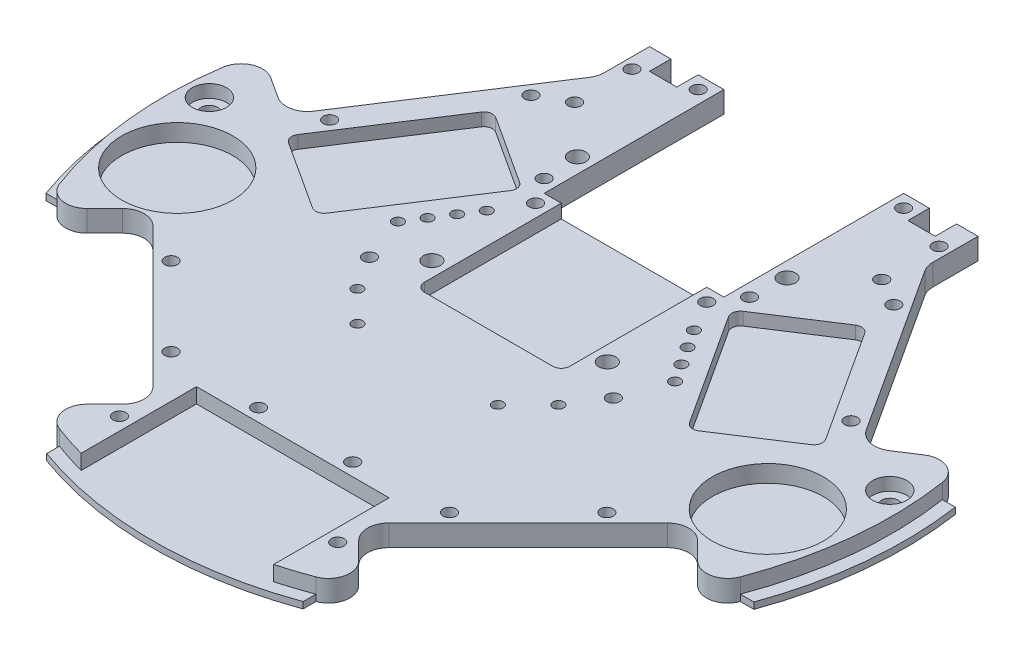
SolidWorks part; units mm, degrees
material "7079 Alloy"
ref_plane "Front" through (0, 0, 0) normal (0, 0, 1) x (1, 0, 0)
ref_plane "Top" through (0, 0, 0) normal (0, 1, 0) x (1, 0, 0)
ref_plane "Right" through (0, 0, 0) normal (1, 0, 0) x (0, 0, -1)
sketch "Sketch1" plane through (0, 0, 0) normal (0, 1, 0) x (1, 0, 0)
  line L0 (0, 0) -> (85, 0)
  line L1 (0, 85) -> (0, 0)
  line L2 (-85, 0) -> (0, 0)
  line L3 (0, -85) -> (0, 0)
  line L4 (0, 0) -> (60.1041, -60.1041)
  line L5 (0, 0) -> (-60.1041, -60.1041)
  line L6 (0, 0) -> (71.287, 46.2943)
  line L7 (0, 0) -> (-71.287, 46.2943)
  line L8 (54.5179, 65.2134) -> (38.3816, 54.7344)
  line L9 (38.3816, 54.7344) -> (67.2475, 10.2848)
  line L10 (67.2475, 10.2848) -> (82.5581, 20.2277)
  line L11 (76.5484, -36.9505) -> (63.6396, -24.0416)
  line L12 (63.6396, -24.0416) -> (24.0416, -63.6396)
  line L13 (24.0416, -63.6396) -> (36.9505, -76.5484)
  line L14 (-36.9505, -76.5484) -> (-24.0416, -63.6396)
  line L15 (-24.0416, -63.6396) -> (-63.6396, -24.0416)
  line L16 (-63.6396, -24.0416) -> (-76.5484, -36.9505)
  line L17 (-82.5581, 20.2277) -> (-67.2475, 10.2848)
  line L18 (-67.2475, 10.2848) -> (-38.3816, 54.7344)
  line L19 (-38.3816, 54.7344) -> (-54.5179, 65.2134)
  line L20 (-54.5179, 65.2134) -> (2.4596, 65.2134)
  line L21 (2.4596, 65.2134) -> (54.5179, 65.2134)
  line L22 (-38.3816, 54.7344) -> (0, 54.7344)
  line L23 (0, 54.7344) -> (38.3816, 54.7344)
  line L24 (38.3816, 54.7344) -> (38.3816, 75.841)
  line L25 (-38.3816, 75.841) -> (0, 75.841)
  line L26 (-38.3816, 75.841) -> (-38.3816, 54.7344)
  line L27 (0, 75.841) -> (38.3816, 75.841)
  circle A0 centre (0, 0) radius 85
  dimension "D1" = 170
  dimension "D2" = 33
  dimension "D3" = 33
  dimension "D4" = 45
  dimension "D5" = 23
  dimension "D6" = 23
  dimension "D7" = 23
  dimension "D8" = 23
  dimension "D9" = 25
  dimension "D10" = 28
  dimension "D11" = 28
  dimension "D12" = 28
  dimension "D13" = 28
  dimension "D14" = 28
  dimension "D15" = 28
  dimension "D16" = 25
sketch "Sketch2" plane through (0, 0, 0) normal (0, 1, 0) x (1, 0, 0)
  line L0 (82.5581, 20.2277) -> (67.2475, 10.2848)
  line L1 (67.2475, 10.2848) -> (38.3816, 54.7344)
  line L2 (76.5484, -36.9505) -> (63.6396, -24.0416)
  line L3 (63.6396, -24.0416) -> (24.0416, -63.6396)
  line L4 (24.0416, -63.6396) -> (36.9505, -76.5484)
  line L5 (-36.9505, -76.5484) -> (-24.0416, -63.6396)
  line L6 (-24.0416, -63.6396) -> (-63.6396, -24.0416)
  line L7 (-63.6396, -24.0416) -> (-76.5484, -36.9505)
  line L8 (-82.5581, 20.2277) -> (-67.2475, 10.2848)
  line L9 (-67.2475, 10.2848) -> (-38.3816, 54.7344)
  line L10 (-38.3816, 54.7344) -> (-38.3816, 66.7344)
  line L11 (-38.3816, 75.841) -> (-38.3816, 54.7344) construction
  line L12 (-38.3816, 66.7344) -> (38.3816, 66.7344)
  line L13 (38.3816, 54.7344) -> (38.3816, 75.841) construction
  line L14 (38.3816, 66.7344) -> (38.3816, 54.7344)
  arc A0 (82.5581, 20.2277) -> (76.5484, -36.9505) centre (0, 0) cw
  arc A1 (36.9505, -76.5484) -> (-36.9505, -76.5484) centre (0, 0) cw
  arc A2 (-76.5484, -36.9505) -> (-82.5581, 20.2277) centre (0, 0) cw
  dimension "D1" = 12
extrude "Extrude1" add sketch "Sketch2" against normal blind 5
sketch "Sketch3" plane through (0, 0, 0) normal (0, 1, 0) x (1, 0, 0)
  line L0 (-21, 71.7344) -> (-21, 24.7344)
  line L1 (-21, 24.7344) -> (21, 24.7344)
  line L2 (21, 24.7344) -> (21, 71.7344)
  line L3 (21, 71.7344) -> (-21, 71.7344)
  line L4 (38.3816, 66.7344) -> (-38.3816, 66.7344) construction
  dimension "D1" = 21
  dimension "D2" = 21
  dimension "D3" = 42
  dimension "D4" = 5
extrude "Extrude2" cut sketch "Sketch3" against normal up to surface (5 mm away) up to face at (0, -5, 6.7435)
sketch "Sketch4" plane through (0, 0, 0) normal (0, 1, 0) x (-1, 0, 0)
  line L0 (17, 9.2656) -> (17, -30.7344)
  line L2 (17, 9.2656) -> (-17, 9.2656)
  line L3 (17, -30.7344) -> (-17, -30.7344)
  line L4 (-17, -30.7344) -> (-17, 9.2656)
  line L5 (21, -24.7344) -> (-21, -24.7344) construction
  dimension "D1" = 34
  dimension "D2" = 17
  dimension "D3" = 34
  dimension "D4" = 40
extrude "Extrude3" cut sketch "Sketch4" against normal blind 3.2
sketch "Sketch5" plane through (0, 0, 0) normal (0, 1, 0) x (1, 0, 0)
  line L0 (43.4707, -6.3484) -> (62.7601, 6.1783)
  line L1 (62.7601, 6.1783) -> (43.6977, 35.5318)
  line L2 (43.6977, 35.5318) -> (24.4083, 23.0051)
  line L3 (24.4083, 23.0051) -> (43.4707, -6.3484)
  line L5 (67.2475, 10.2848) -> (38.3816, 54.7344) construction
  line L6 (82.5581, 20.2277) -> (67.2475, 10.2848) construction
  dimension "D1" = 6
  dimension "D2" = 35
  dimension "D3" = 23
  dimension "D4" = 1
extrude "Extrude4" cut sketch "Sketch5" against normal blind 3
mirror "Mirror1" about plane through (0, 0, 0) normal (1, 0, 0) of "Extrude4"
sketch "Sketch6" plane through (0, 0, 0) normal (0, 1, 0) x (1, 0, 0)
  line L0 (0, 0) -> (71.287, 46.2943) construction
  line L1 (38.3816, 54.7344) -> (67.2475, 10.2848) construction
  line L2 (63.6396, -24.0416) -> (24.0416, -63.6396) construction
  line L3 (0, 0) -> (60.1041, -60.1041) construction
  circle A0 centre (42.4013, 43.0364) radius 1.5
  circle A1 centre (60.919, 14.5216) radius 1.5
  circle A2 centre (50.9117, -32.5269) radius 1.5
  circle A3 centre (32.5269, -50.9117) radius 1.5
  dimension "D1" = 3
  dimension "D2" = 3
  dimension "D3" = 3
  dimension "D4" = 3
  dimension "D6" = 3
  dimension "D8" = 3
  dimension "D9" = 3
  dimension "D10" = 13
  dimension "D11" = 13
  dimension "D12" = 3
  dimension "D5" = 13
  dimension "D7" = 21
extrude "Extrude5" cut sketch "Sketch6" against normal up to surface (5 mm away) up to face at (0, -5, -3.7521)
mirror "Mirror2" about plane through (0, 0, 0) normal (1, 0, 0) of "Extrude5"
sketch "Sketch7" plane through (0, 0, 0) normal (0, 1, 0) x (-1, 0, 0)
  line L0 (-38.3816, -66.7344) -> (-21, -66.7344) construction
  line L1 (-21, -24.7344) -> (-21, -66.7344) construction
  line L2 (-17, -24.7344) -> (-21, -24.7344) construction
  circle A0 centre (-24, -63.7344) radius 1.5
  circle A1 centre (-24, -27.7344) radius 1.5
  dimension "D2" = 3
  dimension "D3" = 3
  dimension "D4" = 3
  dimension "D5" = 3
  dimension "D6" = 3
  dimension "D1" = 3
extrude "Extrude6" cut sketch "Sketch7" against normal up to surface (5 mm away) up to face at (-50.9117, -5, 31.0269)
mirror "Mirror3" about plane through (0, 0, 0) normal (1, 0, 0) of "Extrude6"
sketch "Sketch8" plane through (0, 0, 0) normal (0, 1, 0) x (1, 0, 0)
  line L0 (33.3816, 68.7344) -> (33.3816, 61.7344)
  line L1 (33.3816, 61.7344) -> (27, 61.7344)
  line L2 (27, 61.7344) -> (27, 68.7344)
  line L3 (27, 68.7344) -> (33.3816, 68.7344)
  line L4 (38.3816, 54.7344) -> (38.3816, 66.7344) construction
  line L5 (38.3816, 66.7344) -> (21, 66.7344) construction
  circle A0 centre (24, 63.7344) radius 1.5 construction
  dimension "D1" = 5
  dimension "D2" = 3
  dimension "D3" = 2
  dimension "D4" = 5
extrude "Extrude7" cut sketch "Sketch8" against normal up to surface (5 mm away) up to face at (-24, -5, -65.2344)
mirror "Mirror4" about plane through (0, 0, 0) normal (1, 0, 0) of "Extrude7"
sketch "Sketch9" plane through (0, 0, 0) normal (0, 1, 0) x (1, 0, 0)
  line L0 (38.3816, 66.7344) -> (33.3816, 66.7344) construction
  line L1 (38.3816, 54.7344) -> (38.3816, 66.7344) construction
  circle A0 centre (35.8816, 60.1344) radius 1.5
  circle A1 centre (35.8816, 46.7344) radius 1.5
  dimension "D1" = 3
  dimension "D2" = 3
  dimension "D3" = 6.6
  dimension "D4" = 13.4
  dimension "D5" = 2.5
extrude "Extrude8" cut sketch "Sketch9" against normal up to surface (5 mm away) up to face at (-24, -5, -29.2344)
mirror "Mirror5" about plane through (0, 0, 0) normal (1, 0, 0) of "Extrude8"
fillet "Fillet1" radius 5 14 edges at (-38.3816, -2.5, -54.7344) (-67.2475, -2.5, -10.2848) (-82.5581, -2.5, -20.2277) (-76.5484, -2.5, 36.9505) (-63.6396, -2.5, 24.0416) (-24.0416, -2.5, 63.6396) (-36.9505, -2.5, 76.5484) (36.9505, -2.5, 76.5484) (24.0416, -2.5, 63.6396) (63.6396, -2.5, 24.0416) (76.5484, -2.5, 36.9505) (82.5581, -2.5, -20.2277) (67.2475, -2.5, -10.2848) (38.3816, -2.5, -54.7344)
fillet "Fillet2" radius 2 10 edges at (-17, -1.6, 9.2656) (17, -1.6, 9.2656) (-43.4707, -1.5, 6.3484) (-24.4083, -1.5, -23.0051) (-43.6977, -1.5, -35.5318) (-62.7601, -1.5, -6.1783) (43.4707, -1.5, 6.3484) (24.4083, -1.5, -23.0051) (43.6977, -1.5, -35.5318) (62.7601, -1.5, -6.1783)
sketch "Sketch11" plane through (0, 0, 0) normal (0, 1, 0) x (1, 0, 0)
  line L3 (-21, 24.7344) -> (-21, 66.7344) construction
  line L4 (21, 24.7344) -> (21, 66.7344) construction
  circle A2 centre (24.5, 36) radius 2
  circle A3 centre (-24.5, 36) radius 2
  dimension "D7" = 4
  dimension "D8" = 4
  dimension "D9" = 3.5
  dimension "D10" = 3.5
extrude "Extrude10" cut sketch "Sketch11" against normal up to surface (5 mm away) up to face at (-35.8816, -5, -61.6344)
sketch "Sketch14" plane through (0, 0, 0) normal (0, 1, 0) x (1, 0, 0)
  line L0 (25.4976, 21.3278) -> (42.3814, -4.671) construction
  line L1 (42.0204, 34.4425) -> (26.0856, 24.0944) construction
  line L2 (25.4976, 21.3278) -> (42.3814, -4.671) construction
  line L5 (64.5243, 14.4782) -> (39.1882, 53.4923) construction
  line L6 (27.5772, -60.1041) -> (60.1041, -27.5772) construction
  line L7 (67.1751, -27.5772) -> (71.3305, -31.7326) construction
  circle A0 centre (24.2035, 14.5256) radius 1.25
  circle A1 centre (29.6499, 6.1389) radius 1.25
  circle A2 centre (23.483, -16.4119) radius 1.25
  circle A3 centre (16.4119, -23.483) radius 1.25
  circle A4 centre (26.9267, 10.3322) radius 1.25
  circle A5 centre (32.3731, 1.9455) radius 1.25
  dimension "D1" = 2.5
  dimension "D3" = 7
  dimension "D4" = 2.5
  dimension "D7" = 33.79
  dimension "D9" = 2.5
  dimension "D10" = 33.79
  dimension "D12" = 10
  dimension "D8" = 2.5
  dimension "D14" = 2.5
  dimension "D16" = 2.5
  dimension "D2" = 4.79
  dimension "D5" = 4.79
  dimension "D6" = 10
  dimension "D11" = 33.79
  dimension "D13" = 23
  dimension "D15" = 5
  dimension "D17" = 5
  dimension "D18" = 4.79
  dimension "D19" = 4.79
sketch "Sketch15" plane through (0, 0, 0) normal (0, 1, 0) x (1, 0, 0)
  circle A0 centre (69, -13) radius 13
  dimension "D1" = 26
  dimension "D2" = 13
  dimension "D3" = 69
extrude "Extrude13" cut sketch "Sketch15" against normal blind 4
mirror "Mirror7" about plane through (0, 0, 0) normal (1, 0, 0) of "Extrude13"
sketch "Sketch16" plane through (0, 0, 0) normal (0, 1, 0) x (1, 0, 0)
  line L1 (-22.5, -55) -> (22.5, -55)
  line L2 (-22.5, -55) -> (-22.5, -95)
  line L3 (-22.5, -95) -> (22.5, -95)
  line L4 (22.5, -55) -> (22.5, -95)
  dimension "D1" = 22.5
  dimension "D2" = 22.5
  dimension "D3" = 55
  dimension "D4" = 40
extrude "Extrude14" cut sketch "Sketch16" against normal blind 3.5
sketch "Sketch17" plane through (0, 0, 0) normal (0, 1, 0) x (1, 0, 0)
  line L0 (22.5, -81.968) -> (22.5, -55) construction
  line L1 (-22.5, -55) -> (-22.5, -81.968) construction
  circle A0 centre (25.5, -70) radius 1.5
  circle A1 centre (-25.5, -70) radius 1.5
  dimension "D1" = 3
  dimension "D2" = 3
  dimension "D3" = 3
  dimension "D4" = 3
  dimension "D5" = 70
extrude "Extrude16" cut sketch "Sketch17" against normal up to surface (5 mm away) up to face at (-24.5, -5, -38)
sketch "Sketch18" plane through (0, 0, 0) normal (0, 1, 0) x (-1, 0, 0)
  line L0 (-22.5, 55) -> (22.5, 55) construction
  line L1 (-22.5, 55) -> (22.5, 55) construction
  circle A0 centre (-11, 52) radius 1.5
  circle A1 centre (11, 52) radius 1.5
  dimension "D1" = 3
  dimension "D2" = 3
  dimension "D3" = 3
  dimension "D4" = 3
  dimension "D5" = 11
  dimension "D6" = 11
extrude "Extrude17" cut sketch "Sketch18" against normal up to surface (5 mm away) up to face at (-25.5, -5, 68.5)
sketch "Sketch20" plane through (0, 0, 0) normal (0, 1, 0) x (1, 0, 0)
  circle A0 centre (20.5, -2) radius 2
  circle A1 centre (-20.5, -2) radius 2
  dimension "D1" = 4
  dimension "D2" = 4
  dimension "D3" = 20.5
  dimension "D4" = 20.5
  dimension "D5" = 2
  dimension "D6" = 2
extrude "Extrude19" cut sketch "Sketch20" against normal up to surface (5 mm away) up to face at (-11, -5, 50.5)
sketch "Sketch23" plane through (0, -5, 0) normal (0, -1, 0) x (1, 0, 0)
  line L0 (84.0358, -12.7663) -> (87.0358, -12.7663)
  line L1 (79.5452, 29.9593) -> (82.7082, 29.9593)
  arc A0 (79.5452, 29.9593) -> (84.0358, -12.7663) centre (0, 0) cw
  arc A1 (84.0358, -12.7663) -> (79.5452, 29.9593) centre (0, 0) ccw construction
  arc A2 (87.0358, -12.7663) -> (82.7082, 29.9593) centre (0, 0) ccw
  dimension "D1" = 3
extrude "Extrude24" add sketch "Sketch23" against normal blind 1.5
mirror "Mirror8" about plane through (0, 0, 0) normal (1, 0, 0) of "Extrude24"
sketch "Sketch24" plane through (0, -5, 0) normal (0, -1, 0) x (1, 0, 0)
  line L0 (-29.9593, 79.5452) -> (-29.9593, 82.5452)
  line L1 (29.9593, 82.5452) -> (29.9593, 79.5452)
  arc A0 (29.9593, 79.5452) -> (-29.9593, 79.5452) centre (0, 0) ccw
  arc A1 (29.9593, 79.5452) -> (-29.9593, 79.5452) centre (0, 0) ccw construction
  arc A2 (-29.9593, 82.5452) -> (29.9593, 82.5452) centre (0, 0) cw
  dimension "D1" = 3
extrude "Extrude25" add sketch "Sketch24" against normal blind 1.5
sketch "Sketch27" plane through (0, 0, 0) normal (0, 1, 0) x (1, 0, 0)
  line L1 (17, 24.7344) -> (21, 24.7344) construction
  line L2 (17, -7.2656) -> (17, 24.7344) construction
  line L3 (-17, 24.7344) -> (-17, -7.2656) construction
  circle A0 centre (20, 21.7344) radius 1.5
  circle A1 centre (-20, 21.7344) radius 1.5
  dimension "D1" = 3
  dimension "D2" = 3
  dimension "D4" = 3
  dimension "D3" = 3
  dimension "D5" = 3
extrude "Extrude26" cut sketch "Sketch27" against normal up to surface (5 mm away) up to face at (-20.5, -5, 0)
sketch "Sketch28" plane through (0, 0, 0) normal (0, 1, 0) x (1, 0, 0)
  circle A0 centre (28.5, -8.6) radius 1.5
  circle A1 centre (11, -52) radius 1.5 construction
  circle A2 centre (-28.5, -8.6) radius 1.5
  circle A3 centre (-11, -52) radius 1.5 construction
  dimension "D2" = 17.5
  dimension "D3" = 3
  dimension "D5" = 3
  dimension "D1" = 43.4
  dimension "D4" = 17.5
extrude "Extrude27" cut sketch "Sketch28" against normal up to surface (5 mm away) up to face at (-20, -5, -23.2344)
sketch "Sketch29" plane through (0, 0, 0) normal (0, 1, 0) x (1, 0, 0)
  circle A0 centre (-79.5, 5) radius 4
  circle A1 centre (79.5, 5) radius 4
  dimension "D2" = 79.5
  dimension "D4" = 8
  dimension "D5" = 8
  dimension "D1" = 5
  dimension "D3" = 79.5
extrude "Extrude28" cut sketch "Sketch29" against normal blind 3
sketch "Sketch30" plane through (0, -3, 0) normal (0, 1, 0) x (1, 0, 0)
  circle A0 centre (79.5, 5) radius 2
  circle A1 centre (-79.5, 5) radius 2
  dimension "D1" = 4
  dimension "D2" = 4
extrude "Extrude29" cut sketch "Sketch30" against normal up to surface (2 mm away) up to face at (-28.5, -5, 7.1)
extrude "Extrude30" cut sketch "Sketch14" against normal up to surface (5 mm away) up to face at (-79.5, -5, -7)
mirror "Mirror9" about plane through (0, 0, 0) normal (1, 0, 0) of "Extrude30"
